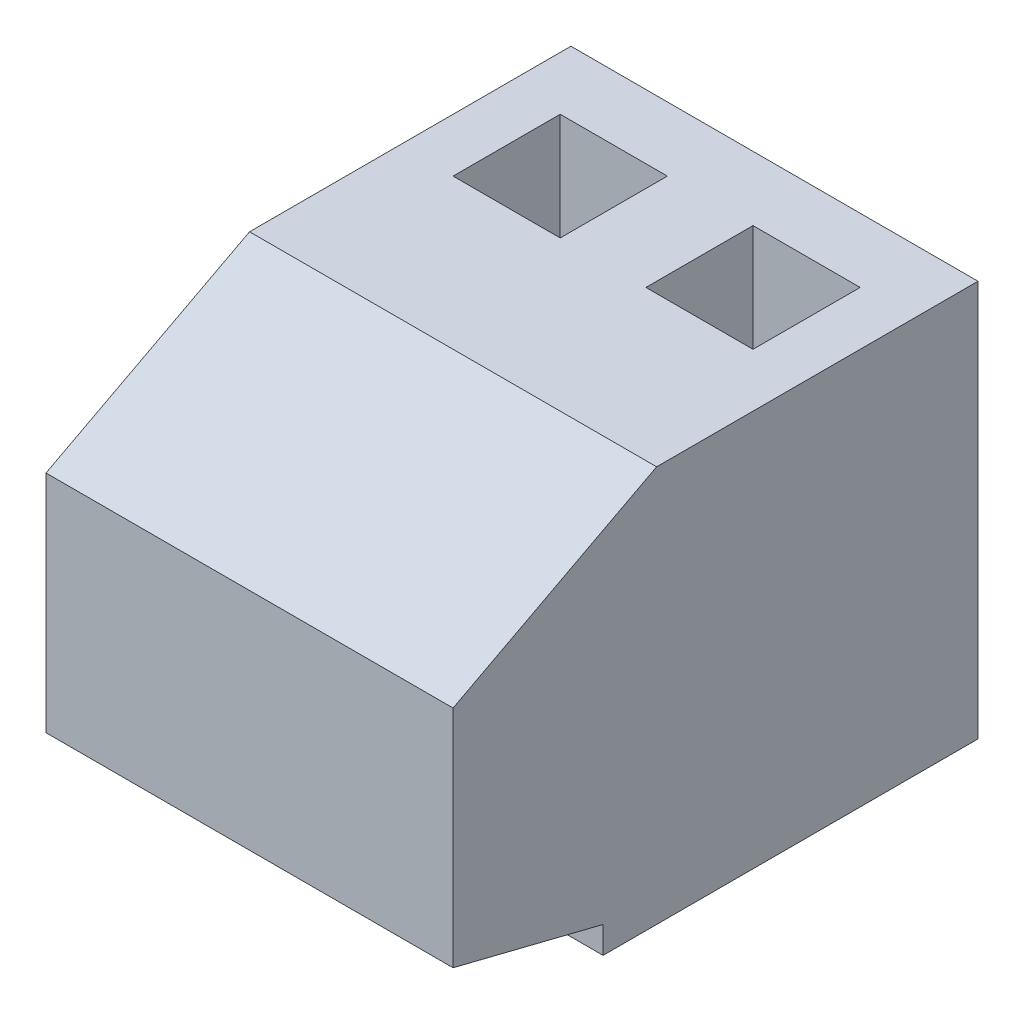
SolidWorks part; units mm, degrees
ref_plane "Front Plane" through (0, 0, 0) normal (0, 0, 1) x (1, 0, 0)
ref_plane "Top Plane" through (0, 0, 0) normal (0, 1, 0) x (1, 0, 0)
ref_plane "Right Plane" through (0, 0, 0) normal (1, 0, 0) x (0, 0, -1)
sketch "Sketch1" plane through (0, 0, 0) normal (0, 0, 1) x (1, 0, 0)
  line L1 (-3.8, 3.7) -> (3.8, 3.7)
  line L2 (-3.8, 3.7) -> (-3.8, -3.7)
  line L3 (-3.8, -3.7) -> (3.8, -3.7)
  line L4 (3.8, 3.7) -> (3.8, -3.7)
  line L5 (-3.8, 3.7) -> (3.8, -3.7) construction
  line L6 (-3.8, -3.7) -> (3.8, 3.7) construction
  point P0 (0, 0)
  dimension "D1" = 7.6
  dimension "D2" = 7.4
extrude "Boss-Extrude1" add sketch "Sketch1" along normal blind 6
sketch "Sketch2" plane through (3.8, 0, 0) normal (1, 0, 0) x (0, 0, -1)
  line L0 (-6, 3.7) -> (-6, -3.7)
  line L1 (-6, -3.7) -> (-7, -3.7)
  line L2 (-7, -3.7) -> (-7, -3.2)
  line L3 (-7, -3.2) -> (-9.8, -2.5)
  line L4 (-9.8, -2.5) -> (-9.8, 1.7)
  line L5 (-9.8, 1.7) -> (-6, 3.7)
  line L6 (-6, 3.7) -> (0, 3.7) construction
  dimension "D1" = 1
  dimension "D2" = 0.5
  dimension "D3" = 3.8
  dimension "D4" = 4.2
  dimension "D5" = 2
extrude "Boss-Extrude2" add sketch "Sketch2" against normal up to surface (7.6 mm away) up to face at (-3.8, 0, 3)
sketch "Sketch3" plane through (0, 3.7, 0) normal (0, 1, 0) x (1, 0, 0)
  line L0 (-3.8, -6) -> (-3.8, 0) construction
  line L1 (-2.8, -1.2) -> (-0.8, -1.2)
  line L2 (-2.8, -1.2) -> (-2.8, -3.2)
  line L3 (-2.8, -3.2) -> (-0.8, -3.2)
  line L4 (-0.8, -1.2) -> (-0.8, -3.2)
  line L5 (-2.8, -1.2) -> (-0.8, -3.2) construction
  line L6 (-2.8, -3.2) -> (-0.8, -1.2) construction
  line L7 (3.8, 0) -> (-3.8, 0) construction
  line L8 (0, 0) -> (0, -6) construction
  line L9 (3.8, -6) -> (-3.8, -6) construction
  line L10 (2.8, -3.2) -> (0.8, -1.2) construction
  line L11 (2.8, -1.2) -> (0.8, -3.2) construction
  line L12 (0.8, -1.2) -> (0.8, -3.2)
  line L13 (2.8, -3.2) -> (0.8, -3.2)
  line L14 (2.8, -1.2) -> (2.8, -3.2)
  line L15 (2.8, -1.2) -> (0.8, -1.2)
  point P0 (-1.8, -2.2)
  point P18 (1.8, -2.2)
  dimension "D1" = 2
  dimension "D2" = 1
  dimension "D3" = 1.2
extrude "Cut-Extrude1" cut sketch "Sketch3" against normal blind 6
